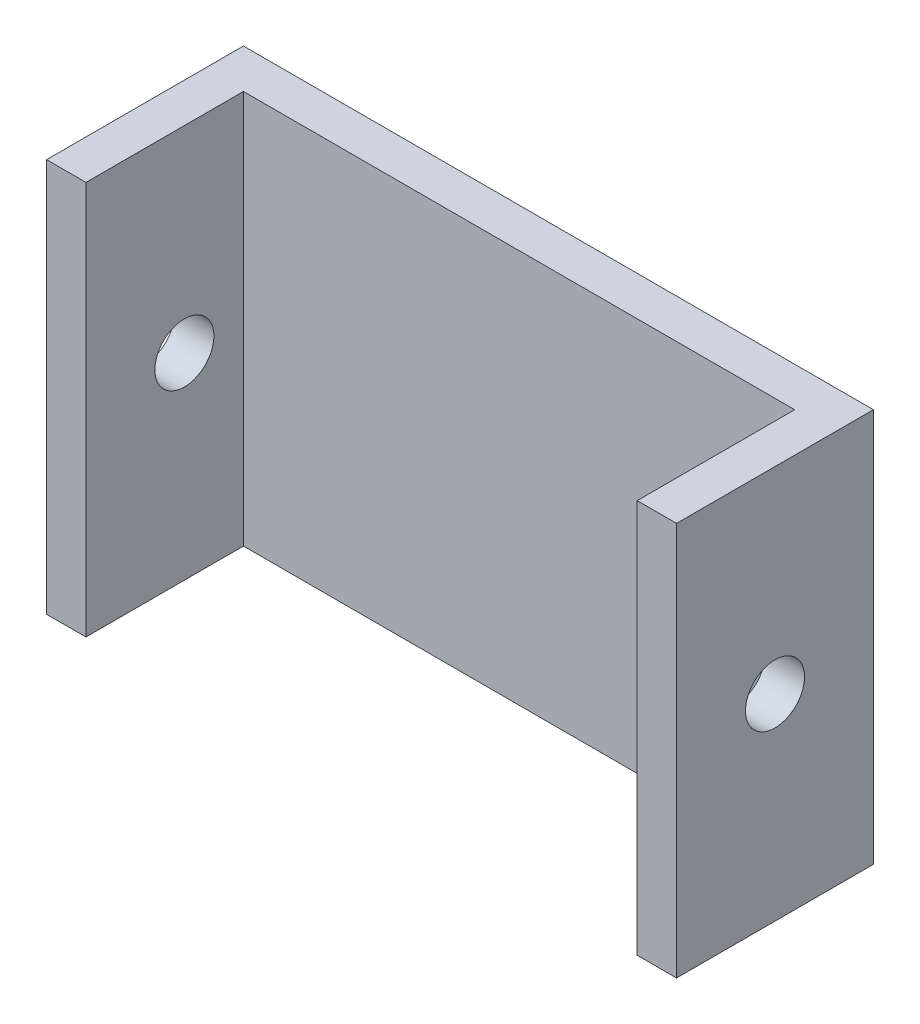
SolidWorks part; units mm, degrees
ref_plane "Plan de face" through (0, 0, 0) normal (0, 0, 1) x (1, 0, 0)
ref_plane "Plan de dessus" through (0, 0, 0) normal (0, 1, 0) x (1, 0, 0)
ref_plane "Plan de droite" through (0, 0, 0) normal (1, 0, 0) x (0, 0, -1)
sketch "Esquisse1" plane through (0, 0, 0) normal (0, 0, 1) x (1, 0, 0)
  line L1 (-14, 10) -> (14, 10)
  line L2 (-14, 10) -> (-14, -10)
  line L3 (-14, -10) -> (14, -10)
  line L4 (14, 10) -> (14, -10)
  line L5 (-14, 10) -> (14, -10) construction
  line L6 (-14, -10) -> (14, 10) construction
  point P0 (0, 0)
  dimension "D1" = 28
  dimension "D2" = 20
extrude "Boss.-Extru.1" add sketch "Esquisse1" along normal blind 2
sketch "Esquisse2" plane through (0, 0, 0) normal (0, 0, 1) x (1, 0, 0)
  line L0 (-14, -10) -> (-16, -10)
  line L1 (-16, -10) -> (-16, 10)
  line L2 (-16, 10) -> (-14, 10)
  line L3 (-14, 10) -> (-14, -10)
  line L8 (0, -13.5768) -> (0, 16.1891) construction
  line L9 (16, 10) -> (14, 10)
  line L10 (16, -10) -> (16, 10)
  line L11 (14, -10) -> (16, -10)
  line L12 (14, 10) -> (14, -10)
  dimension "D1" = 2
extrude "Boss.-Extru.2" add sketch "Esquisse2" along normal blind 10
sketch "Esquisse3" plane through (0, 0, 0) normal (1, 0, 0) x (0, 0, -1)
  circle A0 centre (-5, 0) radius 1.5
  dimension "D2" = 3
  dimension "D1" = 5
extrude "Enlèv. mat.-Extru.1" cut sketch "Esquisse3" against normal through all both and the other way through all
sketch "Esquisse4" plane through (0, 0, 0) normal (0, 0, -1) x (-1, 0, 0)
  line L0 (-16, -10) -> (-16, 10) construction
  line L1 (-16, 10) -> (16, 10) construction
  text T0 "<b>MQ-6 SENSOR</b>" font "Century Gothic" height in points 12
  dimension "D1" = 1
  dimension "D2" = 10
extrude "Enlèv. mat.-Extru.2" cut sketch "Esquisse4" against normal blind 1
